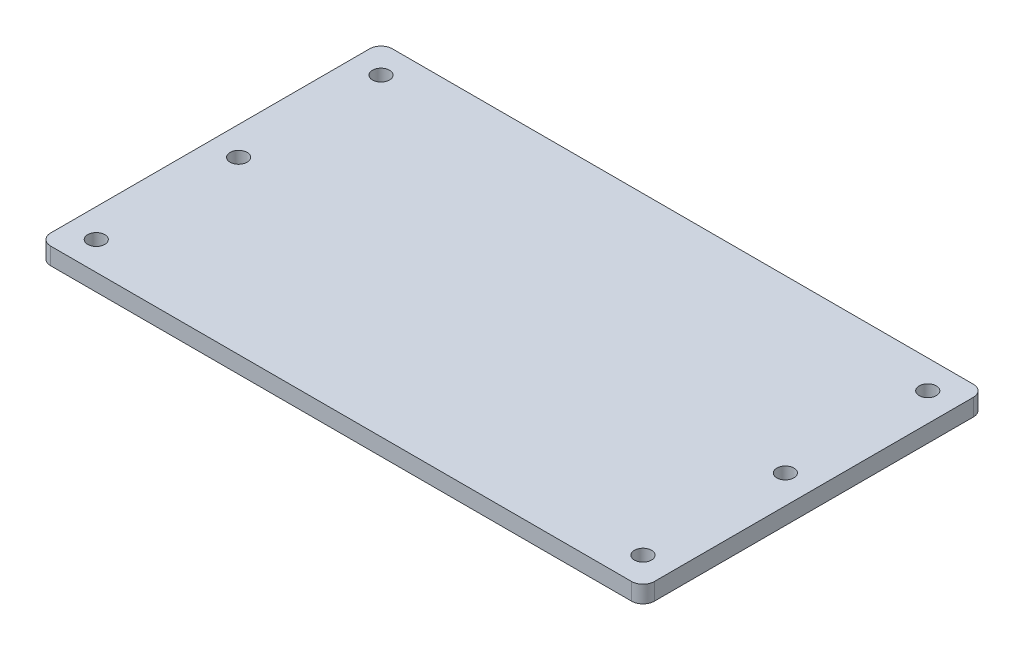
SolidWorks part; units mm, degrees
ref_plane "前视基准面" through (0, 0, 0) normal (0, 0, 1) x (1, 0, 0)
ref_plane "上视基准面" through (0, 0, 0) normal (0, 1, 0) x (1, 0, 0)
ref_plane "右视基准面" through (0, 0, 0) normal (1, 0, 0) x (0, 0, -1)
other "Configuration Table"
sketch "草图1" plane through (0, 0, 0) normal (0, 1, 0) x (1, 0, 0)
  line L1 (-53, 30) -> (53, 30)
  line L2 (-53, 30) -> (-53, -30)
  line L3 (-53, -30) -> (53, -30)
  line L4 (53, 30) -> (53, -30)
  line L5 (-53, 30) -> (53, -30) construction
  line L6 (-53, -30) -> (53, 30) construction
  point P0 (0, 0)
  dimension "D1" = 106
  dimension "D2" = 60
extrude "凸台-拉伸1" add sketch "草图1" along normal blind 3
sketch "草图2" plane through (0, 3, 0) normal (0, 1, 0) x (1, 0, 0)
  line L0 (53, 30) -> (-53, 30) construction
  line L1 (48, -25) -> (-48, -25) construction
  line L2 (48, -25) -> (48, 25) construction
  line L3 (48, 25) -> (-48, 25) construction
  line L4 (-48, -25) -> (-48, 25) construction
  line L5 (48, -25) -> (-48, 25) construction
  line L6 (48, 25) -> (-48, -25) construction
  line L7 (-53, 30) -> (-53, -30) construction
  line L8 (0, 0) -> (0, 30) construction
  circle A0 centre (-48, 25) radius 1.5
  circle A1 centre (-48, 0) radius 1.5
  circle A2 centre (-48, -25) radius 1.5
  circle A3 centre (48, -25) radius 1.5
  circle A4 centre (48, 0) radius 1.5
  circle A5 centre (48, 25) radius 1.5
  point P2 (0, 0)
  dimension "D1" = 3
  dimension "D2" = 5
  dimension "D3" = 5
extrude "切除-拉伸1" cut sketch "草图2" against normal blind 10
fillet "圆角1" radius 2 4 edges at (53, 1.5, 30) (-53, 1.5, 30) (53, 1.5, -30) (-53, 1.5, -30)
